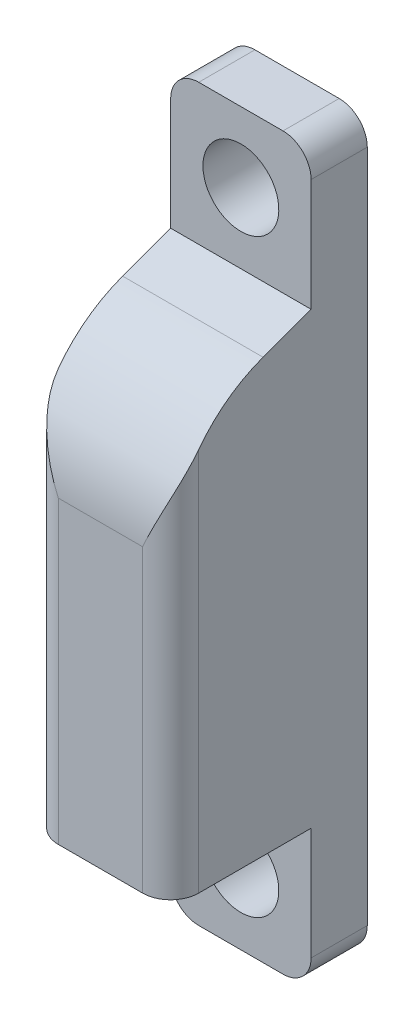
SolidWorks part; units mm, degrees
material "ABS"
ref_plane "Front Plane" through (0, 0, 0) normal (0, 0, 1) x (1, 0, 0)
ref_plane "Top Plane" through (0, 0, 0) normal (0, 1, 0) x (1, 0, 0)
ref_plane "Right Plane" through (0, 0, 0) normal (1, 0, 0) x (0, 0, -1)
sketch "Sketch1" plane through (0, 0, 0) normal (0, 0, 1) x (1, 0, 0)
  line L1 (-2.5, -13) -> (2.5, -13)
  line L2 (-2.5, -13) -> (-2.5, 13)
  line L3 (-2.5, 13) -> (2.5, 13)
  line L4 (2.5, -13) -> (2.5, 13)
  line L5 (-2.5, -13) -> (2.5, 13) construction
  line L6 (-2.5, 13) -> (2.5, -13) construction
  point P0 (0, 0)
  dimension "D1" = 26
  dimension "D2" = 5
extrude "Extrude1" add sketch "Sketch1" along normal blind 7
sketch "Sketch2" plane through (2.5, 0, 0) normal (-1, 0, 0) x (0, 0, 1)
  circle A0 centre (-6.2858, 5.1229) radius 14.4829
extrude "Extrude2" [suppressed] cut sketch "Sketch2" along normal blind 10
hole_wizard "Ø2.7 (2.7) Diameter Hole1" positions "Sketch5" profile "Sketch7" hole size "Ø2.7" standard "GB" end condition through all
sketch "Sketch5" plane through (0, 0, 0) normal (0, 0, -1) x (-1, 0, 0)
  line L0 (0, 10.5) -> (0, -10.5)
  point P0 (0, 10.5)
  point P6 (0, -10.5)
  dimension "D1" = 21
sketch "Sketch7" plane through (0, 10.5, 0) normal (1, 0, 0) x (0, 1, 0)
  line L0 (0, 0) -> (0, 7)
  line L1 (0, 7) -> (1.35, 7)
  line L2 (1.35, 7) -> (1.35, 0)
  line L5 (1.35, 0) -> (0, 0)
  line L11 (0, -6.35) -> (0, 107.95) construction
  dimension "Thru Hole Dia." = 2.7
  dimension "Thru Hole Depth" = 7
sketch "Sketch8" plane through (2.5, 0, 0) normal (1, 0, 0) x (0, 0, -1)
  line L0 (0, -13) -> (0, 13) construction
  line L1 (-7, -13) -> (-2, -13)
  line L2 (-7, -13) -> (-7, -8)
  line L3 (-7, -8) -> (-2, -8)
  line L4 (-2, -13) -> (-2, -8)
  line L6 (-7, 13) -> (-2, 13)
  line L7 (-7, 13) -> (-7, 8)
  line L8 (-7, 8) -> (-2, 8)
  line L9 (-2, 13) -> (-2, 8)
  dimension "D1" = 2
  dimension "D2" = 5
extrude "Extrude3" cut sketch "Sketch8" against normal up to surface (5 mm away) up to face at (-2.5, 0, 3.5)
fillet "Fillet3" [suppressed] radius 4
fillet "Fillet1" radius 1 2 edges at (-2.5, 0, 7) (2.5, 0, 7)
fillet "Fillet2" radius 1 4 edges at (2.5, 13, 1) (-2.5, 13, 1) (2.5, -13, 1) (-2.5, -13, 1)
sketch "Sketch9" plane through (-2.5, 0, 0) normal (-1, 0, 0) x (0, 0, 1)
  line L0 (2, 8) -> (3.7101, 7.3776)
  line L1 (7, 8) -> (7, -8) construction
  line L2 (7, 8) -> (7, 2.6791)
  line L3 (7, 8) -> (2, 8)
  arc A0 (7, 2.6791) -> (3.7101, 7.3776) centre (2, 2.6791) ccw
  dimension "D1" = 5
  dimension "D2" = 20
extrude "Extrude4" cut sketch "Sketch9" against normal up to surface (5 mm away) up to face at (2.5, 0, 2.5)
